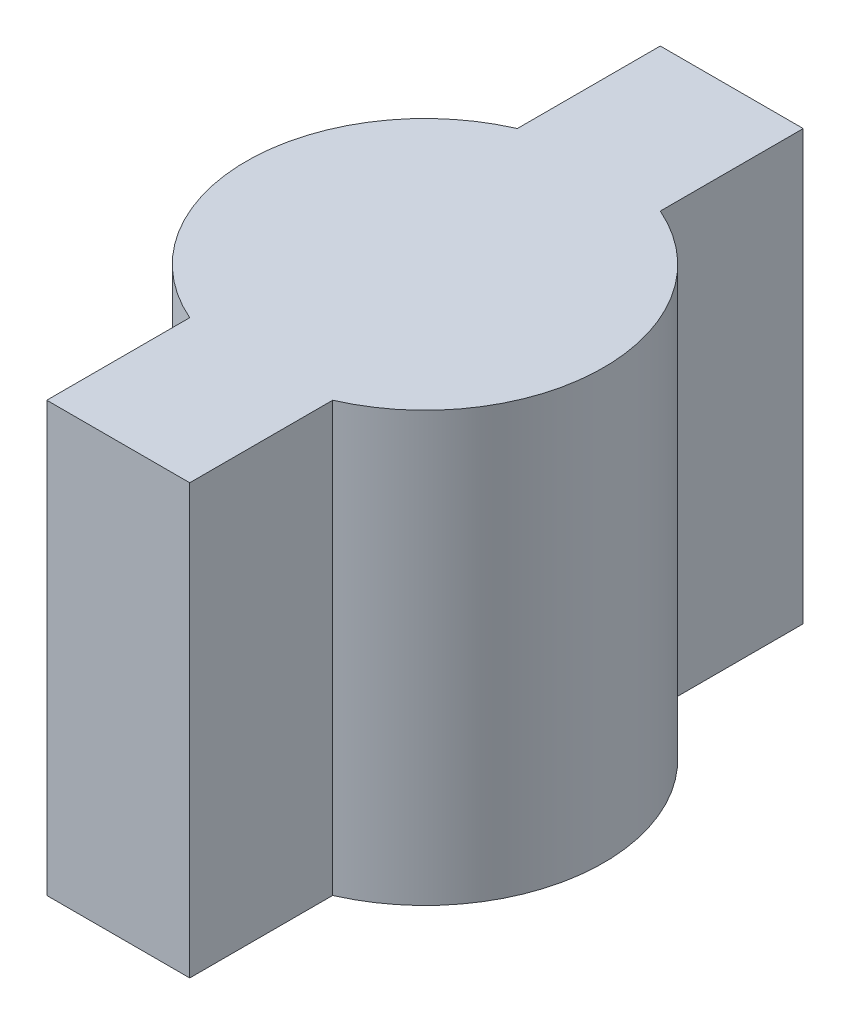
SolidWorks part; units mm, degrees
ref_plane "Front Plane" through (0, 0, 0) normal (0, 0, 1) x (1, 0, 0)
ref_plane "Top Plane" through (0, 0, 0) normal (0, 1, 0) x (1, 0, 0)
ref_plane "Right Plane" through (0, 0, 0) normal (1, 0, 0) x (0, 0, -1)
sketch "Sketch1" plane through (0, 0, 0) normal (0, 1, 0) x (1, 0, 0)
  line L0 (-1, 2.2913) -> (-1, 4.2913)
  line L1 (-1, 4.2913) -> (1, 4.2913)
  line L2 (1, 4.2913) -> (1, 2.2913)
  line L3 (1, -2.2913) -> (1, -4.2913)
  line L4 (1, -4.2913) -> (-1, -4.2913)
  line L5 (-1, -4.2913) -> (-1, -2.2913)
  arc A0 (-1, 2.2913) -> (-1, -2.2913) centre (0, 0) ccw
  arc A1 (1, -2.2913) -> (1, 2.2913) centre (0, 0) ccw
  dimension "D1" = 5
  dimension "D2" = 2
  dimension "D3" = 2
  dimension "D4" = 2
  dimension "D5" = 2
extrude "Boss-Extrude1" add sketch "Sketch1" along normal blind 6
sketch "Sketch3" plane through (0, 0, 0) normal (0, -1, 0) x (1, 0, 0)
  circle A0 centre (0, 0) radius 2
  dimension "D1" = 4
extrude "Cut-Extrude1" cut sketch "Sketch3" against normal blind 5
